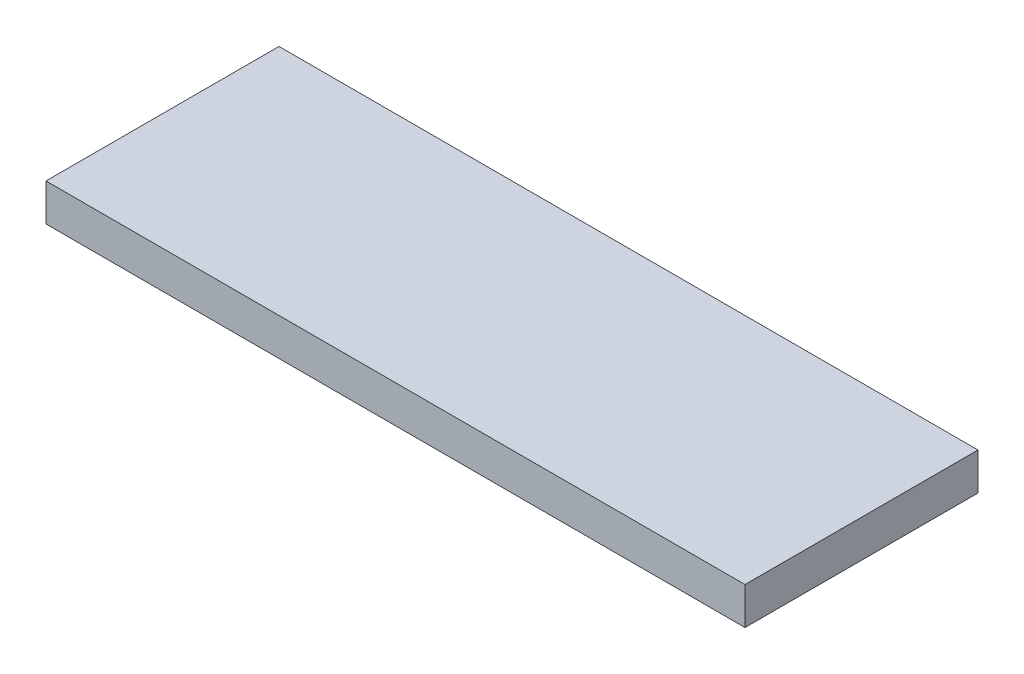
SolidWorks part; units mm, degrees
ref_plane "Alzado" through (0, 0, 0) normal (0, 0, 1) x (1, 0, 0)
ref_plane "Planta" through (0, 0, 0) normal (0, 1, 0) x (1, 0, 0)
ref_plane "Vista lateral" through (0, 0, 0) normal (1, 0, 0) x (0, 0, -1)
sketch "Croquis1" plane through (0, 0, 0) normal (0, 1, 0) x (1, 0, 0)
  line L1 (75, -25) -> (-75, -25)
  line L2 (75, -25) -> (75, 25)
  line L3 (75, 25) -> (-75, 25)
  line L4 (-75, -25) -> (-75, 25)
  line L5 (75, -25) -> (-75, 25) construction
  line L6 (75, 25) -> (-75, -25) construction
  point P0 (0, 0)
  dimension "D1" = 50
  dimension "D2" = 150
extrude "Saliente-Extruir1" add sketch "Croquis1" along normal blind 8
